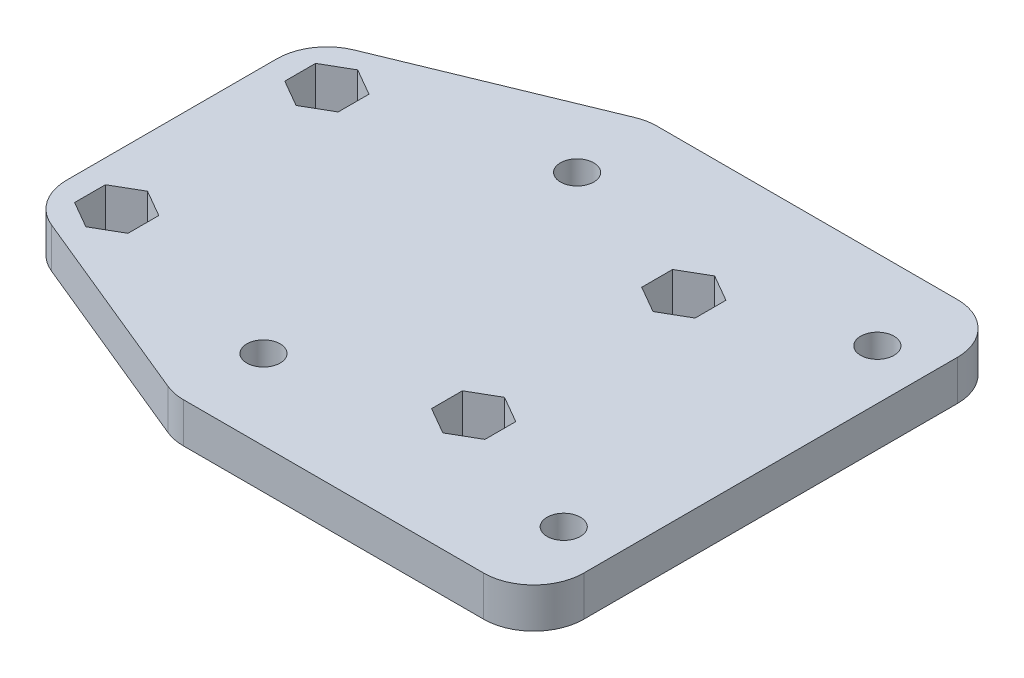
SolidWorks part; units mm, degrees
ref_plane "Front Plane" through (0, 0, 0) normal (0, 0, 1) x (1, 0, 0)
ref_plane "Top Plane" through (0, 0, 0) normal (0, 1, 0) x (1, 0, 0)
ref_plane "Right Plane" through (0, 0, 0) normal (1, 0, 0) x (0, 0, -1)
sketch "Sketch1" plane through (0, 0, 0) normal (0, 1, 0) x (1, 0, 0)
  line L0 (-25, -23.5) -> (-20, -23.5) construction
  line L7 (20, -23.5) -> (25, -23.5) construction
  line L10 (20, 23.5) -> (25, 23.5) construction
  line L13 (-25, 23.5) -> (-20, 23.5) construction
  line L16 (-59.75, 15.75) -> (-59.75, -15.75)
  line L17 (-55.1056, -22.6851) -> (-25.3556, -34.9351)
  line L18 (-22.5, -35.5) -> (22.5, -35.5)
  line L19 (30, -28) -> (30, 28)
  line L20 (22.5, 35.5) -> (-22.5, 35.5)
  line L21 (-25.3556, 34.9351) -> (-55.1056, 22.6851)
  circle A0 centre (-52.25, 15.75) radius 2.75
  circle A1 centre (-52.25, -15.75) radius 2.75
  circle A2 centre (1.25, -15.75) radius 2.75
  circle A3 centre (1.25, 15.75) radius 2.75
  circle A4 centre (-22.5, -23.5) radius 2.5
  circle A5 centre (22.5, -23.5) radius 2.5
  circle A6 centre (22.5, 23.5) radius 2.5
  circle A7 centre (-22.5, 23.5) radius 2.5
  circle A12 centre (-52.25, 15.75) radius 7.5
  circle A13 centre (-52.25, -15.75) radius 7.5
  circle A14 centre (-22.5, -28) radius 7.5
  circle A15 centre (22.5, -28) radius 7.5
  circle A16 centre (22.5, 28) radius 7.5
  circle A17 centre (-22.5, 28) radius 7.5
  dimension "D1" = 15
extrude "Boss-Extrude1" add sketch "Sketch1" along normal blind 6 contours A12 A0 | A17 L21 A12 L16 A13 L17 A14 L18 A15 L19 A16 L20 A3 A2 | A13 A1 | A14 A4 | A15 A5 | A16 A6 | A17 A7
sketch "Sketch2" plane through (0, 6, 0) normal (0, 1, 0) x (1, 0, 0)
  line L1 (-52.25, 11.1312) -> (-48.25, 13.4406)
  line L2 (-48.25, 13.4406) -> (-48.25, 18.0594)
  line L3 (-48.25, 18.0594) -> (-52.25, 20.3688)
  line L4 (-52.25, 20.3688) -> (-56.25, 18.0594)
  line L5 (-56.25, 18.0594) -> (-56.25, 13.4406)
  line L6 (-56.25, 13.4406) -> (-52.25, 11.1312)
  line L7 (-52.25, -11.1312) -> (-56.25, -13.4406)
  line L8 (-56.25, -13.4406) -> (-56.25, -18.0594)
  line L9 (-56.25, -18.0594) -> (-52.25, -20.3688)
  line L10 (-52.25, -20.3688) -> (-48.25, -18.0594)
  line L11 (-48.25, -18.0594) -> (-48.25, -13.4406)
  line L12 (-48.25, -13.4406) -> (-52.25, -11.1312)
  line L13 (-2.75, -18.0594) -> (1.25, -20.3688)
  line L14 (1.25, -20.3688) -> (5.25, -18.0594)
  line L15 (5.25, -18.0594) -> (5.25, -13.4406)
  line L16 (5.25, -13.4406) -> (1.25, -11.1312)
  line L17 (1.25, -11.1312) -> (-2.75, -13.4406)
  line L18 (-2.75, -13.4406) -> (-2.75, -18.0594)
  line L19 (1.25, 11.1312) -> (5.25, 13.4406)
  line L20 (5.25, 13.4406) -> (5.25, 18.0594)
  line L21 (5.25, 18.0594) -> (1.25, 20.3688)
  line L22 (1.25, 20.3688) -> (-2.75, 18.0594)
  line L23 (-2.75, 18.0594) -> (-2.75, 13.4406)
  line L24 (-2.75, 13.4406) -> (1.25, 11.1312)
  circle A0 centre (-52.25, 15.75) radius 4 construction
  circle A1 centre (-52.25, -15.75) radius 4 construction
  circle A2 centre (1.25, -15.75) radius 4 construction
  circle A3 centre (1.25, 15.75) radius 4 construction
  dimension "D1" = 8
extrude "Cut-Extrude1" cut sketch "Sketch2" against normal through all and the other way through all
